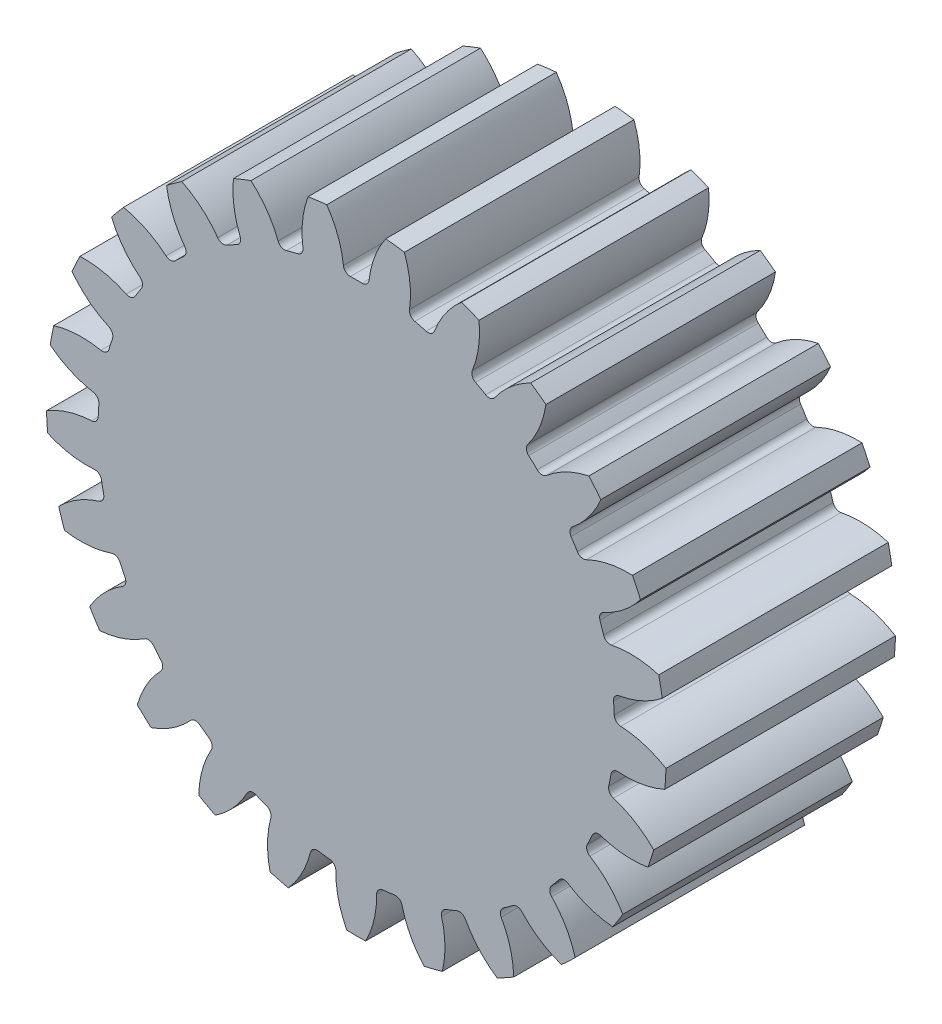
SolidWorks part; units mm, degrees
ref_plane "Front Plane" through (0, 0, 0) normal (0, 0, 1) x (1, 0, 0)
ref_plane "Top Plane" through (0, 0, 0) normal (0, 1, 0) x (1, 0, 0)
ref_plane "Right Plane" through (0, 0, 0) normal (1, 0, 0) x (0, 0, -1)
sketch "Sketch1" plane through (0, 0, 0) normal (0, 0, 1) x (1, 0, 0)
  circle A0 centre (0, 0) radius 25
  circle A1 centre (0, 0) radius 27
  circle A3 centre (0, 0) radius 22.5
  circle A4 centre (0, 0) radius 28
  point P5 (0, 0)
  dimension "D1" = 50
  dimension "D2" = 54
  dimension "D3" = 4.5
  dimension "D4" = 1
extrude "Boss-Extrude2" add sketch "Sketch1" along normal mid plane 20 contours A1
sketch "Sketch4" plane through (0, 0, 0) normal (0, 0, 1) x (1, 0, 0)
  line L0 (0, 0) -> (0, 28) construction
  line L1 (-1.5698, 24.9507) -> (1.5698, 24.9507) construction
  line L2 (0, 0) -> (-1.072, 22.4744) construction
  line L3 (0, 20.6378) -> (-2.6344, 27.8758) construction
  line L4 (0, 0) -> (3.5093, 27.7792) construction
  line L5 (1.5698, 24.9507) -> (4.6845, 24.5572) construction
  arc A0 (3.3153, 27.803) -> (-3.3153, 27.803) centre (0, 0) ccw
  arc A1 (-3.3153, 27.803) -> (-1.072, 22.4744) centre (-9.4743, 22.0737) cw
  arc A2 (3.3153, 27.803) -> (1.072, 22.4744) centre (9.4743, 22.0737) ccw
  circle A3 centre (0, 0) radius 22.5 construction
  arc A4 (1.072, 22.4744) -> (-1.072, 22.4744) centre (0, 0) ccw
  circle A5 centre (0, 0) radius 28 construction
  circle A6 centre (0, 0) radius 25 construction
  arc A7 (3.5093, 27.7792) -> (3.3153, 27.803) centre (0, 0) ccw construction
  dimension "D1" = 20
  dimension "D2" = 7.2
extrude "Cut-Extrude1" cut sketch "Sketch4" against normal through all both and the other way through all
fillet "Fillet1" radius 0.6 2 edges at (1.072, 22.4744, 0) (-1.072, 22.4744, 0)
pattern_circular "CirPattern1" count 25 over 360 about axis through (0, 0, 0) along (0, 0, 1) of "Cut-Extrude1", "Fillet1"
equation "\"Module\"= 2mm"
equation "\"Number of Teeth\"= 25"
equation "\"D1@Sketch1\"=\"Module\" * \"Number of Teeth\""
equation "\"D2@Sketch4\"=180 / \"Number of Teeth\""
equation "\"D1@Fillet1\"=.3 * \"Module\""
equation "\"D1@CirPattern1\"=\"Number of Teeth\""
